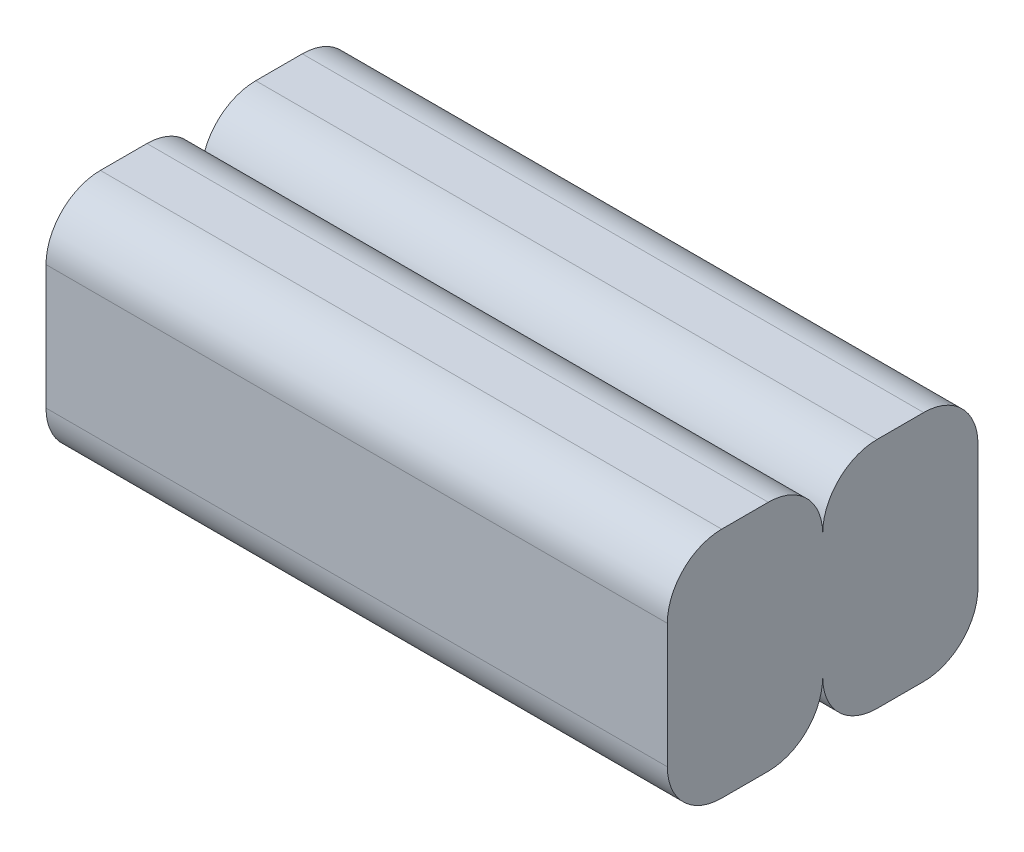
SolidWorks part; units mm, degrees
ref_plane "前视基准面" through (0, 0, 0) normal (0, 0, 1) x (1, 0, 0)
ref_plane "上视基准面" through (0, 0, 0) normal (0, 1, 0) x (1, 0, 0)
ref_plane "右视基准面" through (0, 0, 0) normal (1, 0, 0) x (0, 0, -1)
sketch "草图1" plane through (0, 0, 0) normal (1, 0, 0) x (0, 0, -1)
  line L0 (0, 0) -> (0, 20.5979) construction
  line L1 (20, -15) -> (7, -15)
  line L2 (20, -15) -> (20, 15)
  line L3 (20, 15) -> (7, 15)
  line L4 (-20, -15) -> (-20, 15)
  line L5 (20, -15) -> (-20, 15) construction
  line L6 (20, 15) -> (-20, -15) construction
  line L7 (0, 0) -> (-15.7743, 0) construction
  line L8 (-7, 15) -> (-20, 15)
  line L9 (-7, -15) -> (-20, -15)
  arc A0 (7, 15) -> (0, 8) centre (7, 8) ccw
  arc A1 (-7, 15) -> (0, 8) centre (-7, 8) cw
  arc A2 (-7, -15) -> (0, -8) centre (-7, -8) ccw
  arc A3 (7, -15) -> (0, -8) centre (7, -8) cw
  point P0 (0, 0)
  dimension "D3" = 14
  dimension "D1" = 30
  dimension "D2" = 40
extrude "凸台-拉伸1" add sketch "草图1" along normal blind 80
fillet "圆角1" radius 7 1 edges at (40, 15, -20)
fillet "圆角2" radius 7 1 edges at (40, 15, 20)
fillet "圆角3" radius 7 1 edges at (40, -15, -20)
fillet "圆角4" radius 7 1 edges at (40, -15, 20)
